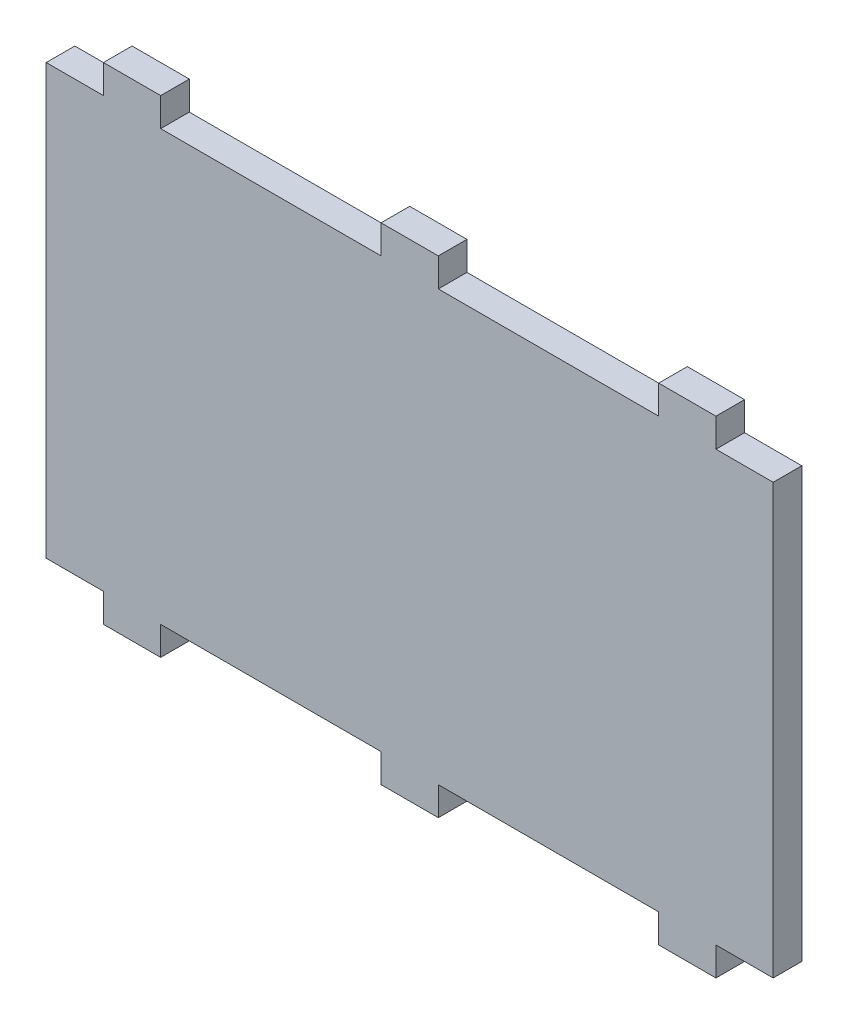
SolidWorks part; units mm, degrees
ref_plane "Plan de face" through (0, 0, 0) normal (0, 0, 1) x (1, 0, 0)
ref_plane "Plan de dessus" through (0, 0, 0) normal (0, 1, 0) x (1, 0, 0)
ref_plane "Plan de droite" through (0, 0, 0) normal (1, 0, 0) x (0, 0, -1)
sketch "Esquisse1" plane through (0, 0, 0) normal (0, 0, 1) x (1, 0, 0)
  line L1 (0, 0) -> (127, 0)
  line L2 (0, 0) -> (0, 75)
  line L3 (0, 75) -> (127, 75)
  line L4 (127, 0) -> (127, 75)
  dimension "D1" = 75
  dimension "D2" = 127
extrude "Boss.-Extru.1" add sketch "Esquisse1" along normal blind 5
sketch "Esquisse2" plane through (0, 0, 5) normal (0, 0, 1) x (1, 0, 0)
  line L0 (127, 75) -> (0, 75) construction
  line L1 (10, 75) -> (20, 75)
  line L2 (10, 75) -> (10, 80)
  line L3 (10, 80) -> (20, 80)
  line L4 (20, 75) -> (20, 80)
  line L5 (0, 0) -> (127, 0) construction
  line L6 (117, 75) -> (107, 75)
  line L7 (117, 75) -> (117, 80)
  line L8 (117, 80) -> (107, 80)
  line L9 (107, 75) -> (107, 80)
  line L10 (63.5, 75) -> (63.5, 0) construction
  line L14 (58.5, 75) -> (68.5, 75)
  line L15 (58.5, 75) -> (58.5, 80)
  line L16 (58.5, 80) -> (68.5, 80)
  line L17 (68.5, 75) -> (68.5, 80)
  line L18 (10, 0) -> (20, 0)
  line L19 (10, 0) -> (10, -5)
  line L20 (10, -5) -> (20, -5)
  line L21 (20, 0) -> (20, -5)
  line L22 (0, 75) -> (0, 0) construction
  line L23 (58.5, 0) -> (68.5, 0)
  line L24 (58.5, 0) -> (58.5, -5)
  line L25 (58.5, -5) -> (68.5, -5)
  line L26 (68.5, 0) -> (68.5, -5)
  line L31 (107, 0) -> (117, 0)
  line L32 (107, 0) -> (107, -5)
  line L33 (107, -5) -> (117, -5)
  line L34 (117, 0) -> (117, -5)
  line L35 (127, 0) -> (127, 75) construction
  dimension "D1" = 10
  dimension "D2" = 5
  dimension "D3" = 10
  dimension "D4" = 10
  dimension "D7" = 10
  dimension "D10" = 10
extrude "Boss.-Extru.2" add sketch "Esquisse2" against normal blind 5
